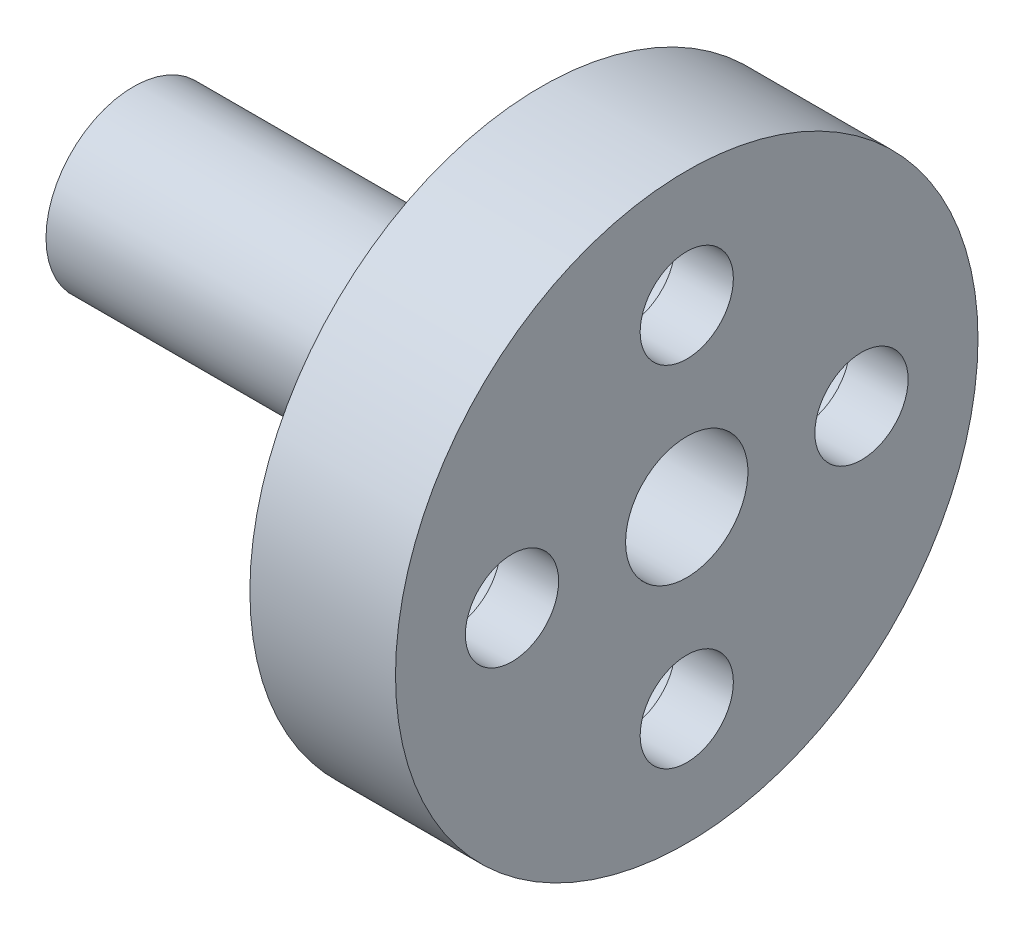
SolidWorks part; units mm, degrees
ref_plane "Front Plane" through (0, 0, 0) normal (0, 0, 1) x (1, 0, 0)
ref_plane "Top Plane" through (0, 0, 0) normal (0, 1, 0) x (1, 0, 0)
ref_plane "Right Plane" through (0, 0, 0) normal (1, 0, 0) x (0, 0, -1)
sketch "Sketch1" plane through (0, 0, 0) normal (0, 0, 1) x (1, 0, 0)
  line L0 (0, 2.1) -> (0, 10)
  line L1 (0, 10) -> (-5, 10)
  line L2 (-5, 10) -> (-5, 3)
  line L3 (-5, 3) -> (-19, 3)
  line L4 (-19, 3) -> (-19, 0)
  line L5 (-19, 0) -> (-13, 0)
  line L6 (-13, 0) -> (-13, 2.1)
  line L7 (-13, 2.1) -> (0, 2.1)
  line L8 (-10, 0) -> (1000, 0) construction
revolve "Revolve1" add sketch "Sketch1" angle 360 about L8
cosmetic thread "Cosmetic Thread1" parameters "D1"=14, "D2"=4.92
sketch "Sketch2" plane through (0, 0, 0) normal (1, 0, 0) x (0, 0, -1)
  circle A0 centre (-6, 0) radius 1.6
  circle A1 centre (6, 0) radius 1.6
  circle A2 centre (0, 6) radius 1.6
  circle A3 centre (0, -6) radius 1.6
extrude "Cut-Extrude1" cut sketch "Sketch2" against normal through all and the other way through all
ref_plane "Plane1" through (-5, 0, 0) normal (1, 0, 0) x (0, 0, -1)
sketch "Sketch3" plane through (-5, 0, 0) normal (1, 0, 0) x (0, 0, -1)
  circle A0 centre (-6, 0) radius 2.85
  circle A1 centre (6, 0) radius 2.85
  circle A2 centre (0, 6) radius 2.85
  circle A3 centre (0, -6) radius 2.85
extrude "Cut-Extrude2" cut sketch "Sketch3" along normal blind 3
